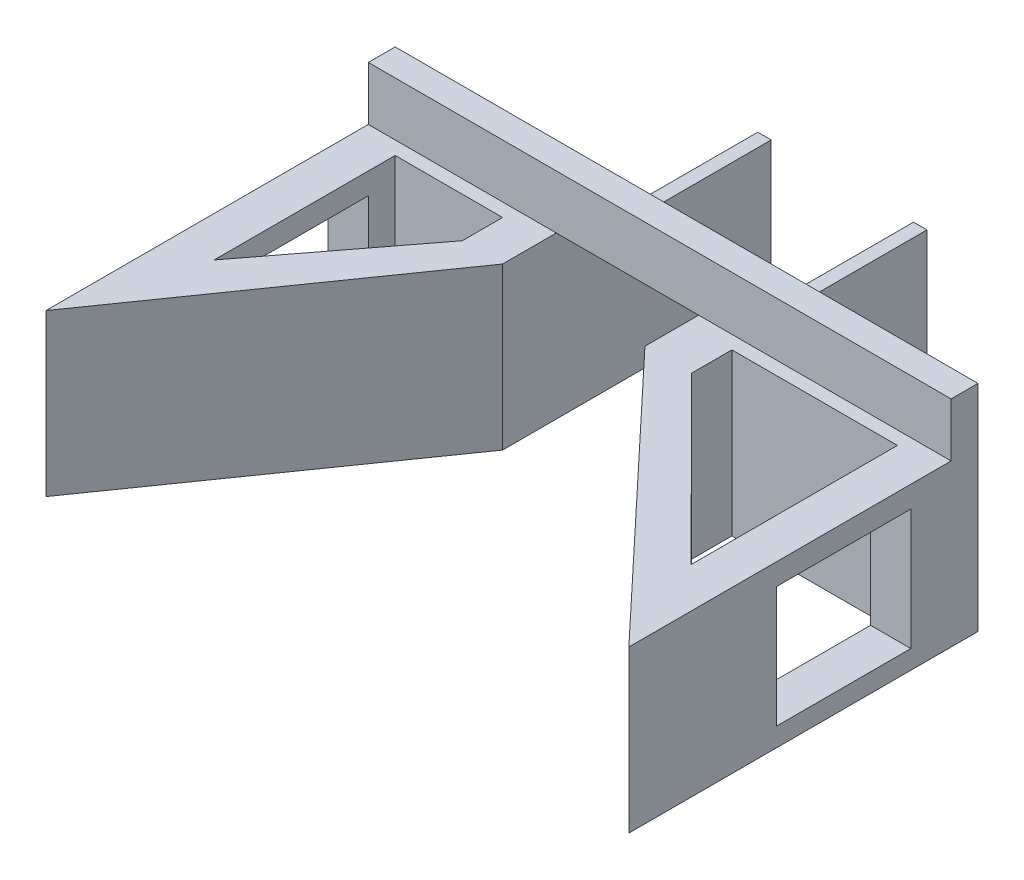
SolidWorks part; units mm, degrees
ref_plane "Front Plane" through (0, 0, 0) normal (0, 0, 1) x (1, 0, 0)
ref_plane "Top Plane" through (0, 0, 0) normal (0, 1, 0) x (1, 0, 0)
ref_plane "Right Plane" through (0, 0, 0) normal (1, 0, 0) x (0, 0, -1)
sketch "Sketch1" plane through (0, 0, 0) normal (0, 1, 0) x (1, 0, 0)
  line L0 (0, 42.7008) -> (0, 27.7008)
  line L1 (0, 42.7008) -> (94, 42.7008)
  line L2 (0, 0) -> (-49.1968, 0) construction
  line L3 (-49.1968, 0) -> (52.6104, 0) construction
  line L4 (-123, 12.7008) -> (-123, -87.2992)
  line L5 (-123, -87.2992) -> (-53, 12.7008)
  line L13 (-123, 42.7008) -> (-53, 42.7008)
  line L14 (-53, 12.7008) -> (-53, 42.7008)
  line L20 (-123, 42.7008) -> (-123, 12.7008)
  line L26 (-108, 27.7008) -> (-108, -39.7137)
  line L27 (-108, -39.7137) -> (-68, 12.7008)
  line L28 (-68, 12.7008) -> (-68, 27.7008)
  line L29 (-68, 27.7008) -> (-108, 27.7008)
  line L39 (94, 42.7008) -> (94, -87.2992)
  line L40 (94, -87.2992) -> (0, 12.7008)
  line L41 (0, 12.7008) -> (0, 27.7008)
  line L42 (79, -49.1437) -> (79, 27.7008)
  line L43 (79, 27.7008) -> (17.3786, 27.7008)
  line L44 (17.3786, 27.7008) -> (17.3786, 12.7008)
  line L45 (17.3786, 12.7008) -> (79, -49.1437)
  dimension "D1" = 53
  dimension "D2" = 70
  dimension "D3" = 100
  dimension "D4" = 30
  dimension "D5" = 15
  dimension "D6" = 15
  dimension "D7" = 15
  dimension "D8" = 15
  dimension "D9" = 94
  dimension "D10" = 15
  dimension "D11" = 15
  dimension "D12" = 15
extrude "Boss-Extrude1" add sketch "Sketch1" along normal blind 60
sketch "Sketch3" plane through (0, 60, 0) normal (0, 1, 0) x (1, 0, 0)
  line L13 (-123, 42.7008) -> (-123, -87.2992) construction
  line L14 (94, 42.7008) -> (-123, 42.7008)
  line L15 (94, 42.7008) -> (94, 32.7008)
  line L16 (94, 32.7008) -> (-123, 32.7008)
  line L17 (-123, 42.7008) -> (-123, 32.7008)
  dimension "D1" = 10
extrude "Boss-Extrude3" add sketch "Sketch3" along normal blind 20
ref_plane "Plane1" through (0, 0, 0) normal (0, -1, 0) x (-1, 0, 0)
sketch "Sketch4" plane through (0, 0, 0) normal (0, -1, 0) x (-1, 0, 0)
  line L1 (53, 42.7008) -> (58, 42.7008)
  line L2 (53, 42.7008) -> (53, 112.7008)
  line L3 (53, 112.7008) -> (58, 112.7008)
  line L4 (58, 42.7008) -> (58, 112.7008)
  dimension "D1" = 70
  dimension "D2" = 5
extrude "Boss-Extrude4" add sketch "Sketch4" against normal blind 50
sketch "Sketch5" plane through (0, 0, 0) normal (0, -1, 0) x (-1, 0, 0)
  line L0 (-94, 42.7008) -> (123, 42.7008) construction
  line L1 (0, 42.7008) -> (-5, 42.7008)
  line L2 (0, 42.7008) -> (0, 112.7008)
  line L3 (0, 112.7008) -> (-5, 112.7008)
  line L4 (-5, 42.7008) -> (-5, 112.7008)
  line L6 (0, 42.7008) -> (0, 12.7008) construction
  dimension "D1" = 5
  dimension "D2" = 70
  dimension "D3" = 0
extrude "Boss-Extrude5" add sketch "Sketch5" against normal blind 50
sketch "Sketch6" plane through (94, 0, 0) normal (1, 0, 0) x (0, 0, -1)
  line L5 (-87.2992, 60) -> (32.7008, 60) construction
  line L6 (-32.2992, 52) -> (17.7008, 52)
  line L7 (-32.2992, 52) -> (-32.2992, 7)
  line L8 (-32.2992, 7) -> (17.7008, 7)
  line L9 (17.7008, 52) -> (17.7008, 7)
  line L10 (42.7008, 80) -> (42.7008, 0) construction
  dimension "D1" = 45
  dimension "D2" = 8
  dimension "D3" = 25
  dimension "D4" = 50
extrude "Cut-Extrude1" cut sketch "Sketch6" against normal blind 30
sketch "Sketch7" plane through (-123, 0, 0) normal (-1, 0, 0) x (0, 0, 1)
  line L0 (-32.7008, 60) -> (87.2992, 60) construction
  line L1 (-17.7008, 52) -> (32.2992, 52)
  line L2 (-17.7008, 52) -> (-17.7008, 7)
  line L3 (-17.7008, 7) -> (32.2992, 7)
  line L4 (32.2992, 52) -> (32.2992, 7)
  line L5 (-42.7008, 50) -> (-42.7008, 0) construction
  dimension "D1" = 45
  dimension "D2" = 50
  dimension "D3" = 8
  dimension "D4" = 25
extrude "Cut-Extrude2" cut sketch "Sketch7" against normal blind 20
